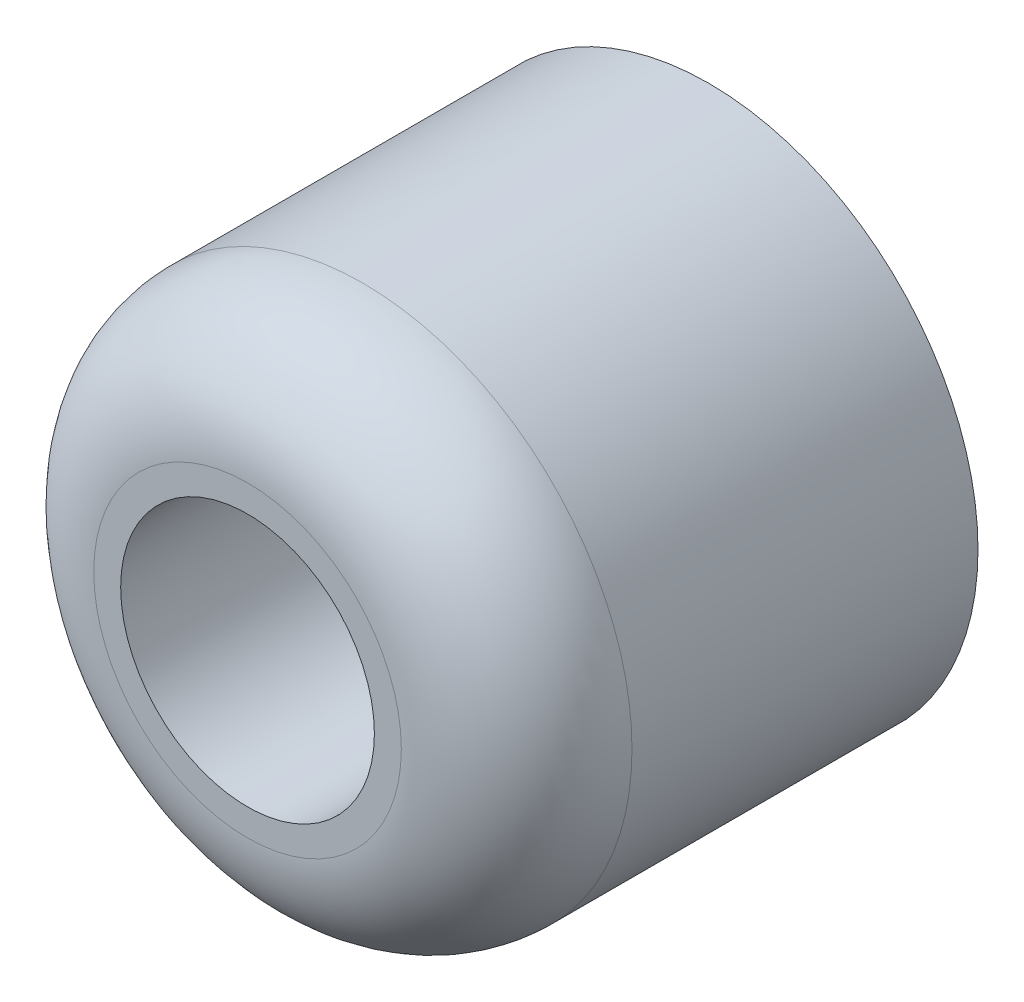
SolidWorks part; units mm, degrees
ref_plane "Front Plane" through (0, 0, 0) normal (0, 0, 1) x (1, 0, 0)
ref_plane "Top Plane" through (0, 0, 0) normal (0, 1, 0) x (1, 0, 0)
ref_plane "Right Plane" through (0, 0, 0) normal (1, 0, 0) x (0, 0, -1)
sketch "Sketch1" plane through (0, 0, 0) normal (0, 0, 1) x (1, 0, 0)
  circle A0 centre (0, 0) radius 1.65
  circle A1 centre (0, 0) radius 3.5
  dimension "D1" = 3.3
  dimension "D2" = 7
extrude "Boss-Extrude1" add sketch "Sketch1" along normal blind 6
fillet "Fillet1" radius 1.5 1 edges at (3.5, 0, 6)
